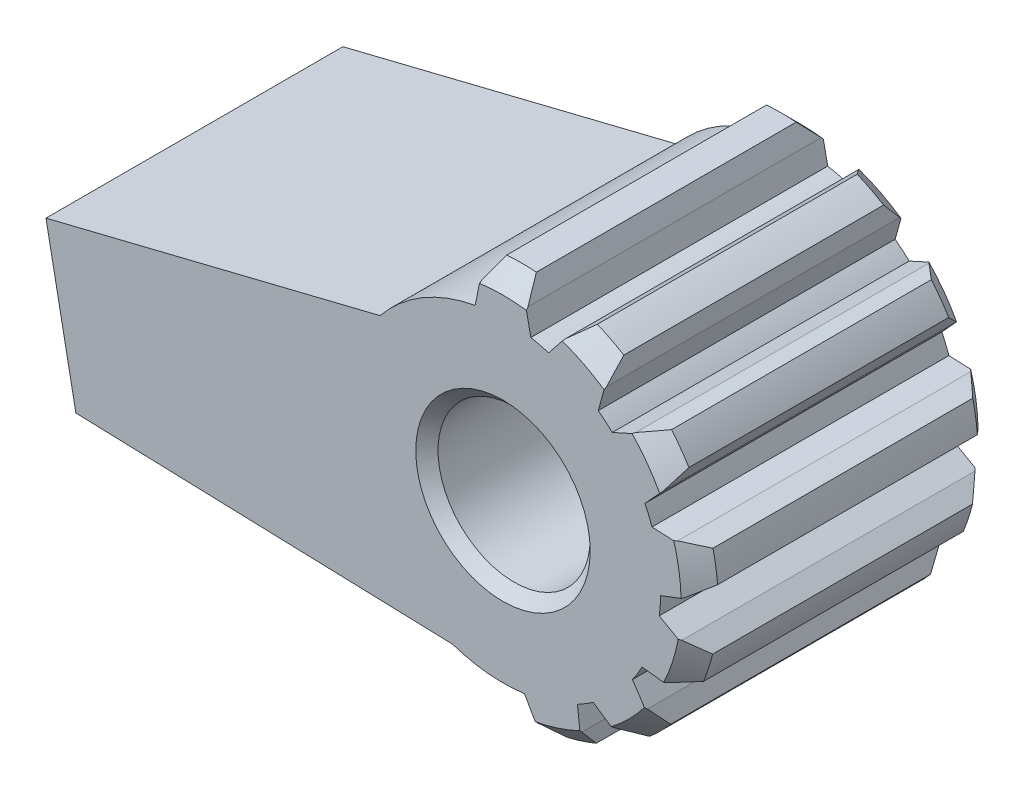
SolidWorks part; units mm, degrees
ref_plane "정면" through (0, 0, 0) normal (0, 0, 1) x (1, 0, 0)
ref_plane "윗면" through (0, 0, 0) normal (0, 1, 0) x (1, 0, 0)
ref_plane "우측면" through (0, 0, 0) normal (1, 0, 0) x (0, 0, -1)
sketch "스케치1" plane through (0, 0, 0) normal (0, 0, 1) x (1, 0, 0)
  line L0 (0, 0) -> (0, 5.3) construction
  line L1 (-0.4, 5.2849) -> (-0.6218, 4.811)
  line L2 (-0.6218, 4.811) -> (-0.75, 4.1833)
  line L3 (0.6218, 4.811) -> (0.75, 4.1833)
  line L4 (0.4, 5.2849) -> (0.6218, 4.811)
  circle A0 centre (0, 0) radius 4.25
  circle A1 centre (0, 0) radius 2.05
  arc A2 (0.4, 5.2849) -> (-0.4, 5.2849) centre (0, 0) ccw
  dimension "D1" = 4.1
  dimension "D2" = 8.5
  dimension "D5" = 5.3
  dimension "D3" = 0.8
  dimension "D4" = 1.5
extrude "보스-돌출1" add sketch "스케치1" along normal mid plane 8
pattern_circular "원형 패턴1" count 7 every 27 about axis through (0, 0, 0) along (0, 0, 1) of "보스-돌출1"
chamfer "모따기1" distance 0.5 angle 45 7 edges at (0, 5.3, -4) (1.6378, -5.0406, -4) (3.7477, -3.7477, -4) (5.0406, -1.6378, -4) (5.2347, 0.8291, -4) (4.2878, 3.1153, -4) (2.4061, 4.7223, -4)
chamfer "모따기2" distance 0.5 angle 45 7 edges at (0, 5.3, 4) (2.4061, 4.7223, 4) (4.2878, 3.1153, 4) (5.2347, 0.8291, 4) (5.0406, -1.6378, 4) (3.7477, -3.7477, 4) (1.6378, -5.0406, 4)
chamfer "모따기3" distance 0.3 angle 45 2 edges at (2.05, 0, 4) (2.05, 0, -4)
sketch "스케치4" plane through (0, 0, 0) normal (0, 0, 1) x (1, 0, 0)
  line L0 (-3.3108, 2.6648) -> (-12.3127, 0.4394)
  line L1 (-12.3127, 0.4394) -> (-11.5081, -3.7068)
  line L2 (-11.5081, -3.7068) -> (-1.3586, -4.027)
  line L3 (-1.3586, -4.027) -> (-3.3108, 2.6648)
  arc A0 (-0.75, 4.1833) -> (0.5794, -4.2103) centre (0, 0) ccw construction
  arc A1 (-0.75, 4.1833) -> (0.5794, -4.2103) centre (0, 0) ccw construction
extrude "보스-돌출2" add sketch "스케치4" along normal mid plane 8 contours L2 L3 L0 L1
